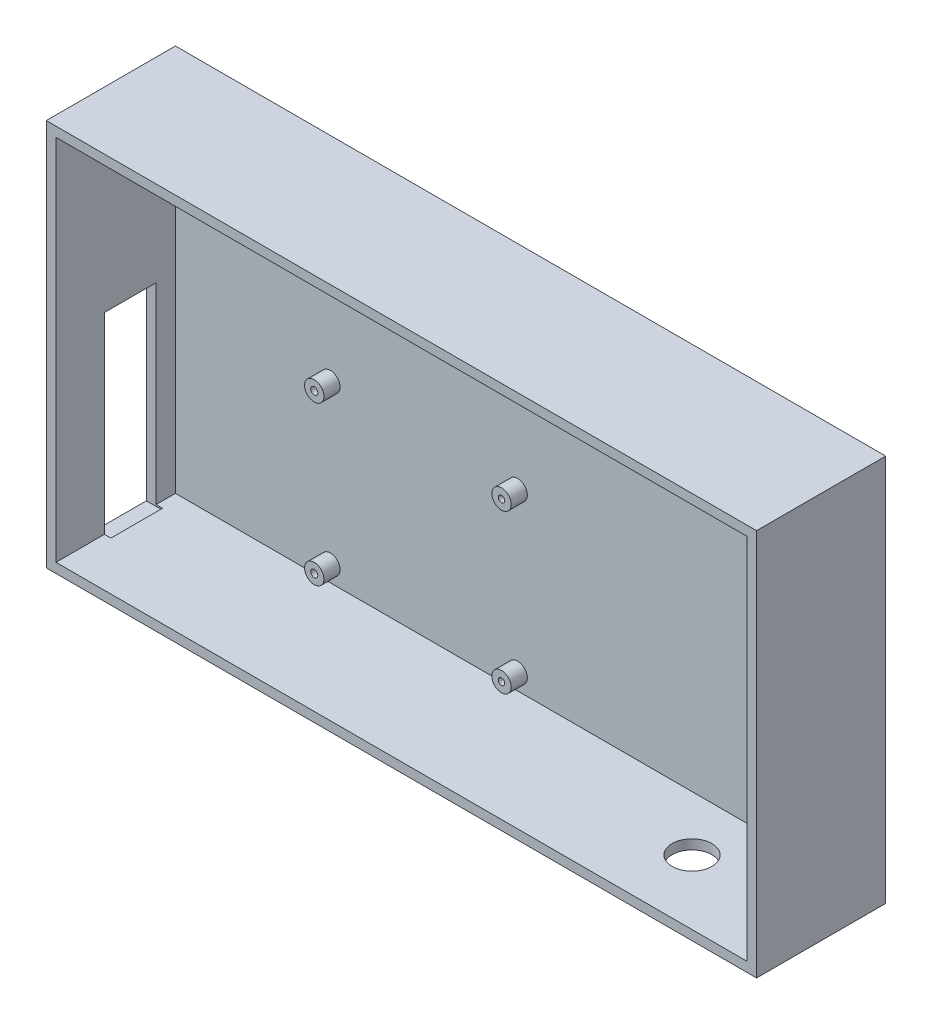
SolidWorks part; units mm, degrees
ref_plane "前视基准面" through (0, 0, 0) normal (0, 0, 1) x (1, 0, 0)
ref_plane "上视基准面" through (0, 0, 0) normal (0, 1, 0) x (1, 0, 0)
ref_plane "右视基准面" through (0, 0, 0) normal (1, 0, 0) x (0, 0, -1)
other "Configuration Table"
sketch "草图1" plane through (0, 0, 0) normal (0, 0, 1) x (1, 0, 0)
  line L1 (-110, -60) -> (110, -60)
  line L2 (-110, -60) -> (-110, 60)
  line L3 (-110, 60) -> (110, 60)
  line L4 (110, -60) -> (110, 60)
  dimension "D1" = 220
  dimension "D2" = 120
extrude "Enclosure" add sketch "草图1" along normal blind 40 separate body
sketch "草图2" plane through (0, 0, 0) normal (0, 0, 1) x (1, 0, 0)
  line L1 (-107, -57) -> (107, -57)
  line L2 (-107, -57) -> (-107, 57)
  line L3 (-107, 57) -> (107, 57)
  line L4 (107, -57) -> (107, 57)
  dimension "D1" = 214
  dimension "D2" = 114
extrude "Cavity" cut sketch "草图2" along normal blind 37 from offset 3
sketch "草图3" plane through (0, 0, 0) normal (0, 0, 1) x (1, 0, 0)
  circle A0 centre (-59, -52) radius 3
  dimension "D1" = 6
extrude "Standoff" add sketch "草图3" along normal blind 8
sketch "草图4" plane through (0, 0, 0) normal (0, 0, 1) x (1, 0, 0)
  circle A0 centre (-59, -52) radius 1.1
  dimension "D1" = 2.2
extrude "StandoffHole" cut sketch "草图4" along normal blind 5 from offset 3
sketch "草图5" plane through (0, 0, 0) normal (0, 0, 1) x (1, 0, 0)
  circle A0 centre (-59, -3) radius 3
  dimension "D1" = 6
extrude "凸台-拉伸3" add sketch "草图5" along normal blind 8
sketch "草图6" plane through (0, 0, 0) normal (0, 0, 1) x (1, 0, 0)
  circle A0 centre (-59, -3) radius 1.1
  dimension "D1" = 2.2
extrude "切除-拉伸3" cut sketch "草图6" along normal blind 5 from offset 3
sketch "草图7" plane through (0, 0, 0) normal (0, 0, 1) x (1, 0, 0)
  circle A0 centre (-1, -52) radius 3
  dimension "D1" = 6
extrude "凸台-拉伸4" add sketch "草图7" along normal blind 8
sketch "草图8" plane through (0, 0, 0) normal (0, 0, 1) x (1, 0, 0)
  circle A0 centre (-1, -52) radius 1
  dimension "D1" = 2
extrude "切除-拉伸4" cut sketch "草图8" along normal blind 5 from offset 3
sketch "草图9" plane through (0, 0, 0) normal (0, 0, 1) x (1, 0, 0)
  circle A0 centre (-1, -3) radius 3
  dimension "D1" = 6
extrude "凸台-拉伸5" add sketch "草图9" along normal blind 8
sketch "草图10" plane through (0, 0, 0) normal (0, 0, 1) x (1, 0, 0)
  circle A0 centre (-1, -3) radius 1
  dimension "D1" = 2
extrude "切除-拉伸5" cut sketch "草图10" along normal blind 5 from offset 3
sketch "草图11" plane through (0, 0, 0) normal (0, 1, 0) x (1, 0, 0)
  circle A0 centre (70, -20) radius 6.15
  dimension "D1" = 12.3
extrude "ButtonHole" cut sketch "草图11" against normal blind 61
sketch "草图12" plane through (0, 0, 0) normal (0, 0, 1) x (1, 0, 0)
  line L1 (-112, -57.5) -> (-105, -57.5)
  line L2 (-112, -57.5) -> (-112, 2.5)
  line L3 (-112, 2.5) -> (-105, 2.5)
  line L4 (-105, -57.5) -> (-105, 2.5)
  dimension "D1" = 7
  dimension "D2" = 60
extrude "Port" cut sketch "草图12" along normal blind 16 from offset 9
